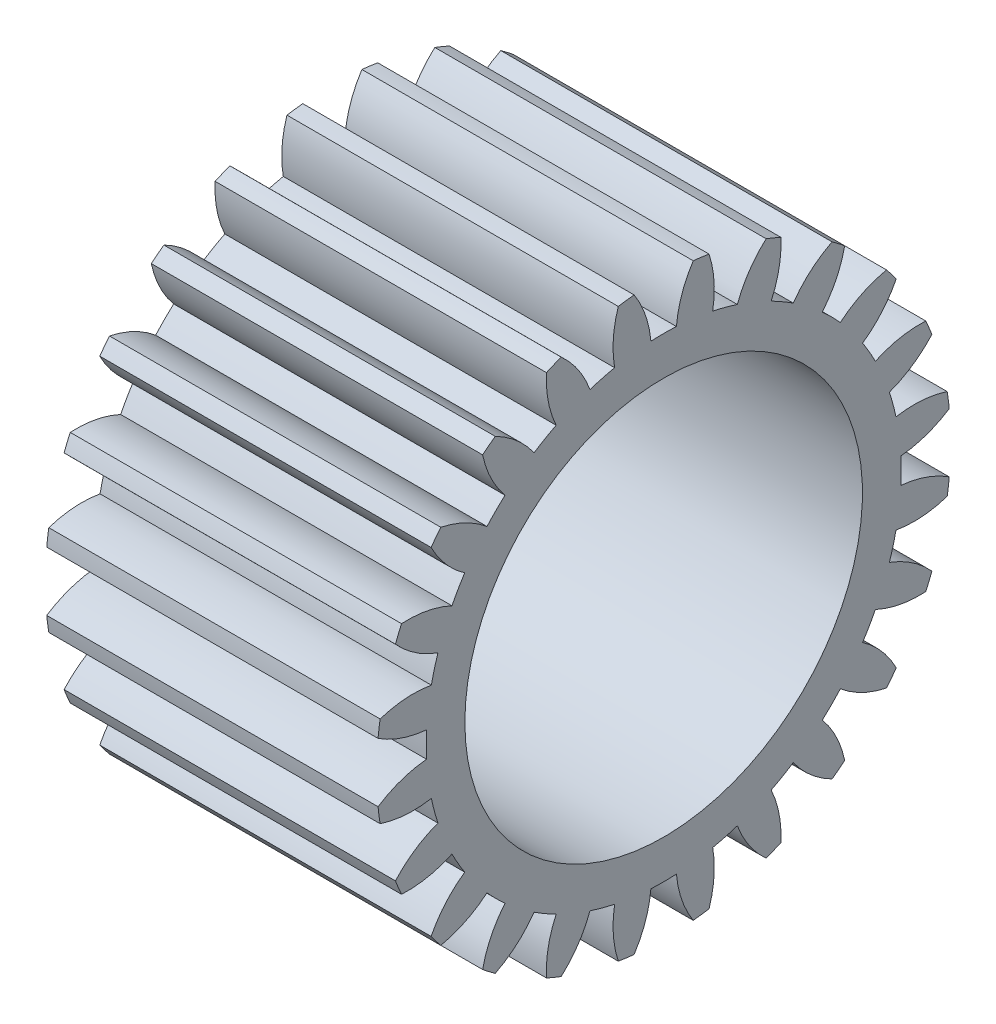
SolidWorks part; units mm, degrees
ref_plane "Plane1" through (0, 0, 0) normal (0, 0, 1) x (1, 0, 0)
ref_plane "Plane2" through (0, 0, 0) normal (0, 1, 0) x (1, 0, 0)
ref_plane "Plane3" through (0, 0, 0) normal (1, 0, 0) x (0, 0, -1)
sketch "HoldingSke" plane through (0, 0, 0) normal (0, 1, 0) x (1, 0, 0)
  line L0 (0, 0) -> (278.4487, -123.9733)
  line L1 (-15, 0) -> (100, 0) construction
  line L2 (0, 0) -> (-2.1039, 2.3779)
  line L3 (0, 0) -> (-11.863, 4.5341)
  line L4 (0, 0) -> (7.8894, 3.5126)
  line L5 (0, 0) -> (-47.5972, -17.7524)
  line L6 (0, 0) -> (-26.3196, -17.7579)
  line L7 (-2.1039, 2.3779) -> (8.8308, 51.9871)
  line L8 (-76.2, 54.61) -> (-33.8074, 54.61)
  line L9 (-67.7845, 28.3722) -> (-49.3413, 33.142)
  line L10 (-76.2, 71.12) -> (104.1128, 71.12)
  line L11 (0, 0) -> (-31.75, 0)
  line L12 (-76.2, 101.6) -> (-76.1147, 101.6)
  line L13 (24.9733, 27.94) -> (52.9518, 28.4284)
  line L14 (24.9733, 27.94) -> (24.9746, 27.94)
  line L15 (24.9733, 27.94) -> (100.4006, 29.5858)
  circle A0 centre (0, 0) radius 19.05
  circle A1 centre (0, 0) radius 22.7529
  circle A2 centre (0, 0) radius 38.1
  circle A3 centre (0, 0) radius 19.05
  dimension "MHD" = 45.5058
  dimension "Hub_dia" = 76.2
  dimension "Bore" = 38.1
  dimension "MBD" = 38.1
  dimension "Num_teeth" = 24
  dimension "Pitch" = 304.8
  dimension "Overall_len" = 50.8
  dimension "Show_teeth" = 24
  dimension "Thickness" = 31.75
  dimension "OAL" = 50.8001
  dimension "T_dim" = 42.3926
  dimension "Ap" = 14.5
  dimension "H" = 19.05
  dimension "Pitch_radius" = 180.3128
  dimension "Width" = 31.75
  dimension "Backlash" = 0.0853
  dimension "Addendum_fac" = 1
  dimension "Dedendum_fac" = 1.25
  dimension "Clearance_fac" = 0.25
  dimension "Dedendum_add" = 0.0013
sketch "BasProSke" plane through (0, 0, 0) normal (0, 1, 0) x (1, 0, 0)
  line L0 (-10, 0) -> (60, 0) construction
  line L1 (0, 0) -> (0, 27.5167)
  line L2 (0, 0) -> (31.75, 0)
  line L3 (31.75, 0) -> (31.75, 27.5167)
  line L4 (31.75, 27.5167) -> (0, 27.5167)
  dimension "Thickness" = 31.75
  dimension "Diameter" = 55.0333
revolve "Base-Revolve" add sketch "BasProSke" angle 360 about L0
sketch "TooCutSke" plane through (0, 0, 0) normal (1, 0, 0) x (0, 0, -1)
  line L1 (0, 0) -> (0, 107) construction
  line L2 (0, 0) -> (-1.8105, 25.3354) construction
  line L3 (0, 0) -> (-6.619, 50.2761) construction
  line L4 (-1.8105, 25.3354) -> (-3.3095, 25.138) construction
  arc A0 (1.2226, 22.72) -> (-1.2226, 22.72) centre (0, 0) ccw
  arc A1 (2.8491, 27.3943) -> (-2.8491, 27.3943) centre (0, 0) ccw
  circle A2 centre (0, 0) radius 25.4 construction
  circle A3 centre (0, 0) radius 24.591 construction
  arc A4 (-1.2226, 22.72) -> (-2.8491, 27.3943) centre (-11.3426, 21.8188) ccw
  arc A5 (2.8491, 27.3943) -> (1.2226, 22.72) centre (11.3426, 21.8188) ccw
  dimension "Root_dia" = 45.5058
  dimension "Overcut_dia" = 55.0841
  dimension "Pitch_dia" = 50.8
  dimension "Base_dia" = 49.1819
  dimension "Flank_rad" = 10.16
  dimension "Half_ang" = 7.5
  dimension "Half_CT" = 1.5119
extrude "ToothCut" cut sketch "TooCutSke" along normal through all
fillet "Breaks" [suppressed] radius 0.0423
fillet "RootFillets" [suppressed] radius 0.5304
pattern_circular "TeethCuts" count 24 every 15 about axis through (-10, 0, 0) along (1, 0, 0) of "ToothCut", "RootFillets", "Breaks"
sketch "HubNeaOneSke" plane through (0, 0, 0) normal (-1, 0, 0) x (0, 0, 1)
  circle A0 centre (0, 0) radius 22.7529
  dimension "Diameter" = 45.5058
extrude "HubNearOne" [suppressed] add sketch "HubNeaOneSke" along normal blind 19.0501
sketch "HubNeaBotSke" plane through (0, 0, 0) normal (-1, 0, 0) x (0, 0, 1)
  circle A0 centre (0, 0) radius 22.7529
  dimension "Diameter" = 45.5058
extrude "HubNearBoth" [suppressed] add sketch "HubNeaBotSke" along normal blind 9.525
ref_plane "FarPln" through (31.75, 0, 0) normal (1, 0, 0) x (0, 0, -1)
sketch "HubFarSke" plane through (31.75, 0, 0) normal (1, 0, 0) x (0, 0, -1)
  circle A0 centre (0, 0) radius 22.7529
  dimension "Diameter" = 45.5058
extrude "HubFar" [suppressed] add sketch "HubFarSke" along normal blind 9.525
sketch "BorSke" plane through (0, 0, 0) normal (1, 0, 0) x (0, 0, -1)
  circle A0 centre (0, 0) radius 19.05
  dimension "Diameter" = 38.1
extrude "Bore" cut sketch "BorSke" along normal mid plane 101.6001
sketch "KeySke" plane through (0, 0, 0) normal (1, 0, 0) x (0, 0, -1)
  line L0 (-4.7625, 0) -> (-4.7625, 23.3426)
  line L1 (-4.7625, 23.3426) -> (4.7625, 23.3426)
  line L2 (4.7625, 23.3426) -> (4.7625, 0)
  line L3 (0, 0) -> (0, 34) construction
  line L4 (-4.7625, 0) -> (4.7625, 0)
  dimension "Offset" = 23.3426
  dimension "Width" = 9.525
extrude "Keyway" [suppressed] cut sketch "KeySke" along normal mid plane 101.6001
pattern_circular "Keyway2" [suppressed] count 2 every 90 about axis through (-10, 0, 0) along (1, 0, 0)
equation "' \"Pitch@HoldingSke\" = 4"
equation "' \"Num_teeth@HoldingSke\" = 12"
equation "' \"Ap@HoldingSke\" =  20"
equation "' \"Ap@HoldingSke\" = 20"
equation "' \"Width@HoldingSke\" = 0.5"
equation "' \"Hub_dia@HoldingSke\"= 1"
equation "' \"Hub_dia@HoldingSke\" = 1"
equation "' \"Overall_len@HoldingSke\" = 1.0"
equation "' \"Bore@HoldingSke\" = 0.75"
equation "' \"T_dim@HoldingSke\" = 0.85"
equation "' \"Width@KeySke\" = 0.25"
equation "' \"Show_teeth@HoldingSke\" = 13"
equation "' \"Backlash@HoldingSke\" = 0.009"
equation "' \"Addendum_fac@HoldingSke\" = 1.0"
equation "' \"Dedendum_fac@HoldingSke\" = 1.25"
equation "' \"Dedendum_add@HoldingSke\" = 0.00005"
equation "' \"Clearance_fac@HoldingSke\" = 0.25"
equation "' \"Pitch@HoldingSke\" = 0.5"
equation "' \"Num_teeth@HoldingSke\" = 23"
equation "' \"Show_teeth@HoldingSke\" = 23"
equation "' \"Backlash@HoldingSke\" = 0.0375"
equation "\"Overcut_dia@TooCutSke\" = (\"Num_teeth@HoldingSke\" + 2 * \"Addendum_fac@HoldingSke\") / \"Pitch@HoldingSke\" + 0.002"
equation "\"Pitch_dia@TooCutSke\" = \"Num_teeth@HoldingSke\" / \"Pitch@HoldingSke\""
equation "\"Base_dia@TooCutSke\" = \"Num_teeth@HoldingSke\" / \"Pitch@HoldingSke\" * cos((\"Ap@HoldingSke\"  * 3.14159265 / 180))"
equation "\"Root_dia@TooCutSke\" = (\"Num_teeth@HoldingSke\" + 2) / \"Pitch@HoldingSke\" - 2 * (\"Addendum_fac@HoldingSke\" + \"Dedendum_fac@HoldingSke\") / \"Pitch@HoldingSke\" - \"Dedendum_add@HoldingSke\" * 2"
equation "\"Half_ang@TooCutSke\" = 180 / \"Num_teeth@HoldingSke\""
equation "\"Half_CT@TooCutSke\" = \"Num_teeth@HoldingSke\" / \"Pitch@HoldingSke\" * sin((3.14159265 / 2 / \"Num_teeth@HoldingSke\")) / 2 - 7 * \"Backlash@HoldingSke\" / 4"
equation "\"Flank_rad@TooCutSke\" = \"Num_teeth@HoldingSke\" / \"Pitch@HoldingSke\" / 5"
equation "\"Radius@RootFillets\" = \"Clearance_fac@HoldingSke\" / \"Pitch@HoldingSke\" + \"Dedendum_add@HoldingSke\""
equation "\"Break_rad@Breaks\" = 0.02 / \"Pitch@HoldingSke\""
equation "\"Thickness@HoldingSke\" = \"Width@HoldingSke\""
equation "\"OAL@HoldingSke\" = \"Thickness@HoldingSke\""
equation "\"MHD@HoldingSke\" = (\"Num_teeth@HoldingSke\" + 2) / \"Pitch@HoldingSke\" - 2 * (\"Addendum_fac@HoldingSke\" + \"Dedendum_fac@HoldingSke\")  / \"Pitch@HoldingSke\" - \"Dedendum_add@HoldingSke\" * 2"
equation "\"MBD@HoldingSke\" = (\"Num_teeth@HoldingSke\" + 2) / \"Pitch@HoldingSke\" - 2 * (\"Addendum_fac@HoldingSke\" + \"Dedendum_fac@HoldingSke\")  / \"Pitch@HoldingSke\" - \"Dedendum_add@HoldingSke\" * 2 - 0.002"
equation "\"MHD@HoldingSke\" = ((sgn( \"MHD@HoldingSke\" - \"Hub_dia@HoldingSke\" )-1)*( \"MHD@HoldingSke\" - \"Hub_dia@HoldingSke\" ))/-2+ \"Hub_dia@HoldingSke\""
equation "\"MBD@HoldingSke\" = ((sgn( \"MBD@HoldingSke\" - \"Bore@HoldingSke\" )-1)*( \"MBD@HoldingSke\" - \"Bore@HoldingSke\" ))/-2+ \"Bore@HoldingSke\""
equation "\"OAL@HoldingSke\" = ((sgn( \"OAL@HoldingSke\" - \"Overall_len@HoldingSke\" )+1)*( \"OAL@HoldingSke\" - \"Overall_len@HoldingSke\" ))/2 + \"Overall_len@HoldingSke\" + 0.000002"
equation "\"Num_teeth@TeethCuts\" = int( \"Show_teeth@HoldingSke\" ) + 1"
equation "\"Num_teeth@TeethCuts\" = ((sgn( \"Num_teeth@TeethCuts\" - \"Num_teeth@HoldingSke\" )-1)*( \"Num_teeth@TeethCuts\" - \"Num_teeth@HoldingSke\" ))/-2+ \"Num_teeth@HoldingSke\""
equation "\"Num_teeth@TeethCuts\" = ((sgn( \"Num_teeth@TeethCuts\" - 2.0)+1)*( \"Num_teeth@TeethCuts\" - 2.0))/2 +2.0"
equation "\"Angle@TeethCuts\" = 360.0 / \"Num_teeth@HoldingSke\""
equation "\"Diameter@BasProSke\" = (\"Num_teeth@HoldingSke\" + 2 * \"Addendum_fac@HoldingSke\") / \"Pitch@HoldingSke\""
equation "\"Thickness@BasProSke\"  = \"Thickness@HoldingSke\""
equation "' \"Fillet_rad@BasProSke\" =  \"Thickness@HoldingSke\" * 0.05"
equation "' \"Fillet_rad@BasProSke\" = \"Thickness@HoldingSke\" * 0.05"
equation "\"MHD@HoldingSke\" = ((sgn( \"MHD@HoldingSke\" - \"Root_dia@TooCutSke\" )-1)*( \"MHD@HoldingSke\" - \"Root_dia@TooCutSke\" ))/-2+ \"Root_dia@TooCutSke\""
equation "\"Diameter@HubNeaOneSke\" = \"MHD@HoldingSke\""
equation "\"Length@HubNearOne\" = \"OAL@HoldingSke\" - \"Thickness@BasProSke\""
equation "\"Diameter@HubNeaBotSke\" = \"MHD@HoldingSke\""
equation "\"Length@HubNearBoth\" = ( \"OAL@HoldingSke\" - \"Thickness@BasProSke\" ) / 2.0"
equation "\"Thickness@FarPln\" = \"Thickness@BasProSke\""
equation "\"Diameter@HubFarSke\" = \"MHD@HoldingSke\""
equation "\"Length@HubFar\" = ( \"OAL@HoldingSke\" - \"Thickness@BasProSke\" ) / 2.0"
equation "\"Diameter@BorSke\" = \"MBD@HoldingSke\""
equation "\"D1@Bore\" = \"OAL@HoldingSke\" * 2.0"
equation "\"D1@Keyway\" = \"OAL@HoldingSke\" * 2.0"
equation "\"Offset@KeySke\" = \"T_dim@HoldingSke\" - \"MBD@HoldingSke\" / 2.0"
